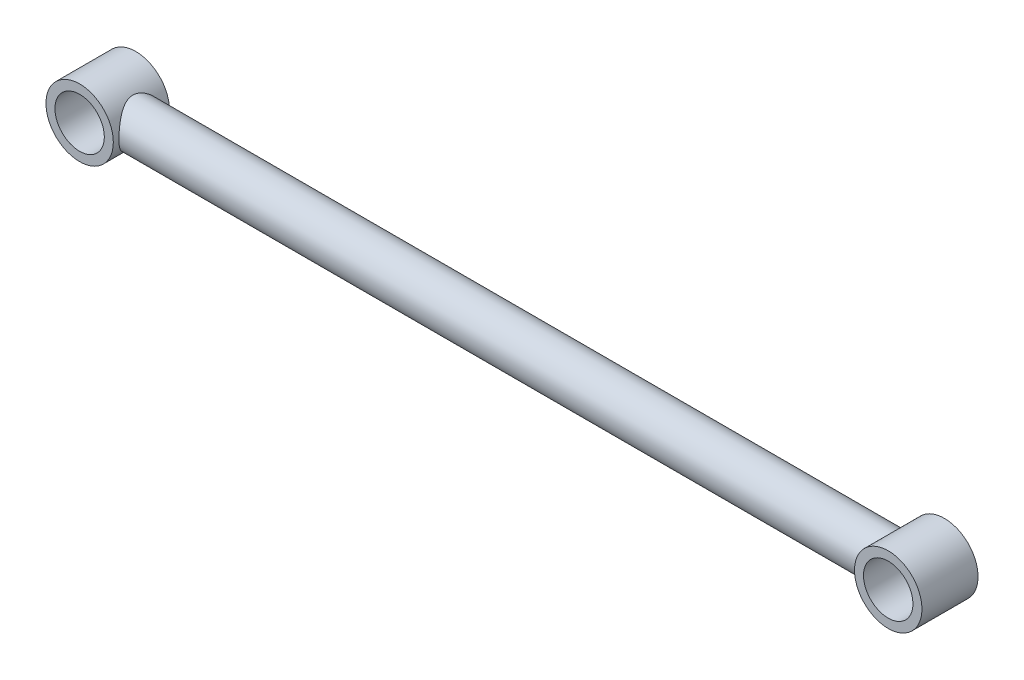
SolidWorks part; units mm, degrees
ref_plane "Front Plane" through (0, 0, 0) normal (0, 0, 1) x (1, 0, 0)
ref_plane "Top Plane" through (0, 0, 0) normal (0, 1, 0) x (1, 0, 0)
ref_plane "Right Plane" through (0, 0, 0) normal (1, 0, 0) x (0, 0, -1)
other "Bounding Box"
ref_plane "Default Plane" through (-123.825, -9.525, -7.9375) normal (0, 1, 0) x (1, 0, 0)
sketch "Sketch3" plane through (0, 0, 0) normal (0, 0, 1) x (1, 0, 0)
  line L0 (0, 0) -> (0, 19.7502) construction
  circle A0 centre (-114.3, 0) radius 6.985
  circle A1 centre (-114.3, 0) radius 9.525
  circle A2 centre (114.3, 0) radius 9.525
  circle A3 centre (114.3, 0) radius 6.985
  dimension "D1" = 13.97
  dimension "D3" = 114.3
  dimension "D2" = 2.54
extrude "Boss-Extrude1" add sketch "Sketch3" along normal mid plane 15.875
sketch "Sketch4" plane through (0, 0, 0) normal (1, 0, 0) x (0, 0, -1)
  circle A0 centre (0, 0) radius 6.35
  dimension "D1" = 12.7
extrude "Boss-Extrude2" add sketch "Sketch4" against normal up to surface and the other way up to surface up to face at (-104.775, 0, 7.9375) other way up to face at (104.775, 0, 7.9375)
